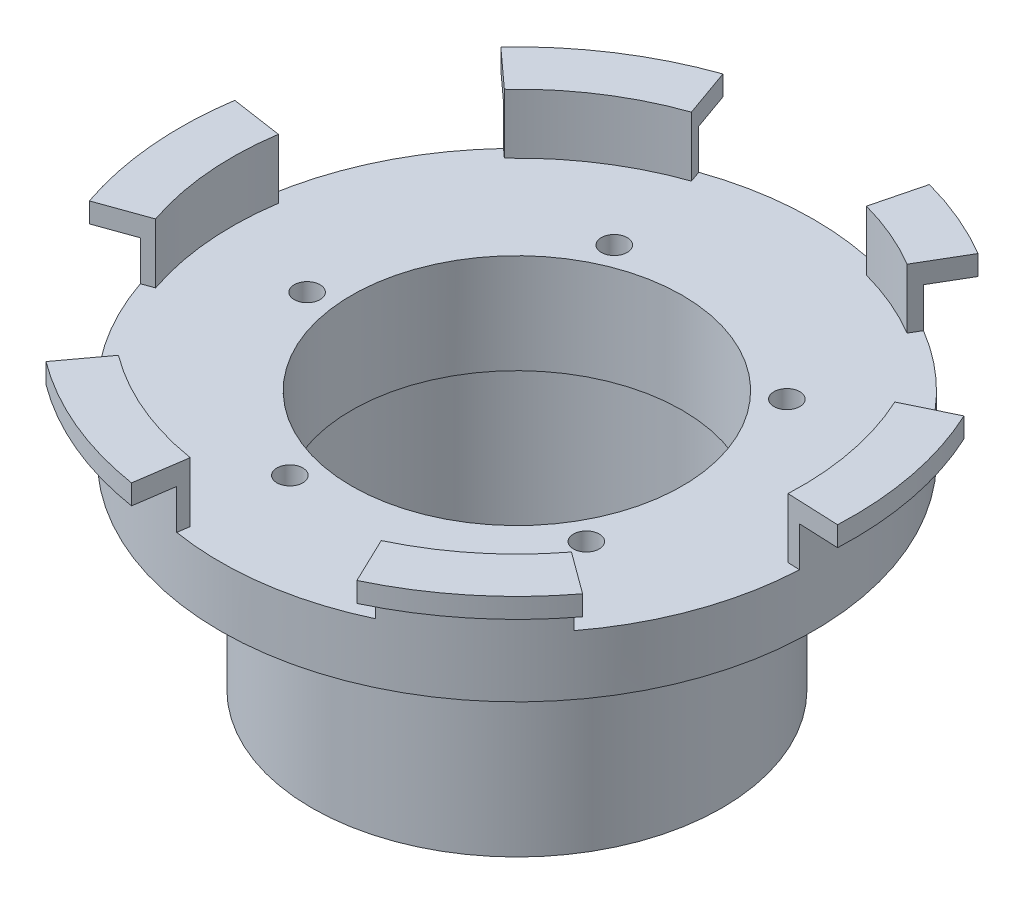
SolidWorks part; units mm, degrees
material "ABS PC"
ref_plane "Front Plane" through (0, 0, 0) normal (0, 0, 1) x (1, 0, 0)
ref_plane "Top Plane" through (0, 0, 0) normal (0, 1, 0) x (1, 0, 0)
ref_plane "Right Plane" through (0, 0, 0) normal (1, 0, 0) x (0, 0, -1)
sketch "Sketch1" plane through (0, 0, 0) normal (0, 1, 0) x (1, 0, 0)
  circle A0 centre (-1.3362, 19.9052) radius 41.5
  circle A1 centre (-1.3362, 19.9052) radius 71.5
  circle A2 centre (40.1859, -4.1762) radius 3.25
  circle A3 centre (34.3976, 51.9535) radius 3.25
  circle A4 centre (-20.7736, 63.7936) radius 3.25
  circle A5 centre (-49.083, 14.9815) radius 3.25
  circle A6 centre (-11.408, -27.0262) radius 3.25
  circle A7 centre (-1.3362, 19.9052) radius 41.5 construction
  point P2 (0, 0)
  dimension "D1" = 6.5
  dimension "D2" = 30
extrude "Boss-Extrude1" add sketch "Sketch1" along normal blind 15
sketch "Sketch3" plane through (0, 0, 0) normal (0, -1, 0) x (1, 0, 0)
  circle A0 centre (-1.3362, -19.9052) radius 71.5 construction
  circle A1 centre (-1.3362, -19.9052) radius 71.5
  circle A2 centre (-1.3362, -19.9052) radius 74.5
  dimension "D1" = 3
extrude "Boss-Extrude2" add sketch "Sketch3" against normal blind 30
sketch "Sketch4" plane through (0, 30, 0) normal (0, 1, 0) x (1, 0, 0)
  circle A0 centre (-1.3362, 19.9052) radius 74.5 construction
  circle A1 centre (-1.3362, 19.9052) radius 74.5
  circle A2 centre (-1.3362, 19.9052) radius 84.5
  dimension "D1" = 10
extrude "Boss-Extrude3" add sketch "Sketch4" against normal blind 5
sketch "Sketch5" plane through (0, 0, 0) normal (0, -1, 0) x (1, 0, 0)
  circle A0 centre (-1.3362, -19.9052) radius 41.5 construction
  circle A1 centre (-1.3362, -19.9052) radius 41.5
  circle A2 centre (-1.3362, -19.9052) radius 51.5
  dimension "D1" = 10
extrude "Boss-Extrude4" add sketch "Sketch5" along normal blind 50
sketch "Sketch6" plane through (0, -50, 0) normal (0, -1, 0) x (1, 0, 0)
  circle A0 centre (-1.3362, -19.9052) radius 41.5 construction
  circle A1 centre (-1.3362, -19.9052) radius 41.5
  circle A2 centre (-1.3362, -19.9052) radius 44.5
  dimension "D1" = 3
extrude "Cut-Extrude1" cut sketch "Sketch6" against normal blind 40
sketch "Sketch7" plane through (0, 30, 0) normal (0, 1, 0) x (1, 0, 0)
  line L0 (19.9502, 55.5302) -> (41.7368, 92.603)
  line L1 (36.552, 36.8385) -> (75.2869, 55.5302)
  circle A0 centre (-1.3362, 19.9052) radius 41.5 construction
  circle A1 centre (-1.3362, 19.9052) radius 84.5 construction
  arc A2 (75.2869, 55.5302) -> (41.7368, 92.603) centre (-1.3362, 19.9052) ccw
  arc A3 (36.552, 36.8385) -> (19.9502, 55.5302) centre (-1.3362, 19.9052) ccw
  point P2 (39.6819, 93.7819)
  point P4 (36.552, 95.4349)
  point P6 (0, 0)
  point P7 (0, 0)
  point P9 (77.9769, 49.0545)
  point P10 (36.4684, 37.0243)
  point P13 (42.95, 91.8704)
  point P14 (36.552, 36.8385)
  point P15 (81.0992, 38.4698)
  point P16 (75.2869, 55.5302)
  dimension "D1" = 25
  dimension "D2" = 50
extrude "Cut-Extrude3" cut sketch "Sketch7" against normal up to surface (15 mm away) up to face at (-49.083, 15, -11.7315)
pattern_circular "CirPattern1" count 6 every 62 about axis through (-1.3362, 0, -19.9052) along (0, 1, 0) of "Cut-Extrude3"
